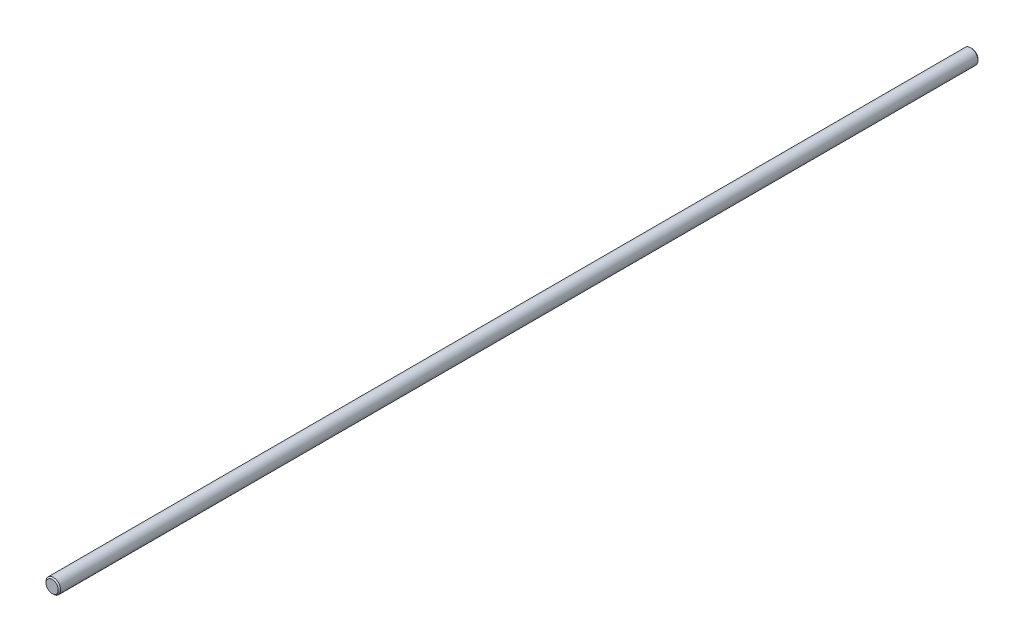
SolidWorks part; units mm, degrees
ref_plane "Front Plane" through (0, 0, 0) normal (0, 0, 1) x (1, 0, 0)
ref_plane "Top Plane" through (0, 0, 0) normal (0, 1, 0) x (1, 0, 0)
ref_plane "Right Plane" through (0, 0, 0) normal (1, 0, 0) x (0, 0, -1)
sketch "Sketch1" plane through (0, 0, 0) normal (0, 0, 1) x (1, 0, 0)
  circle A0 centre (0, 0) radius 6
  dimension "D1" = 12
extrude "Corpo" add sketch "Sketch1" against normal blind 750
chamfer "Chanfros 1x45°" distance 1 angle 45 2 edges at (6, 0, -750) (6, 0, 0)
